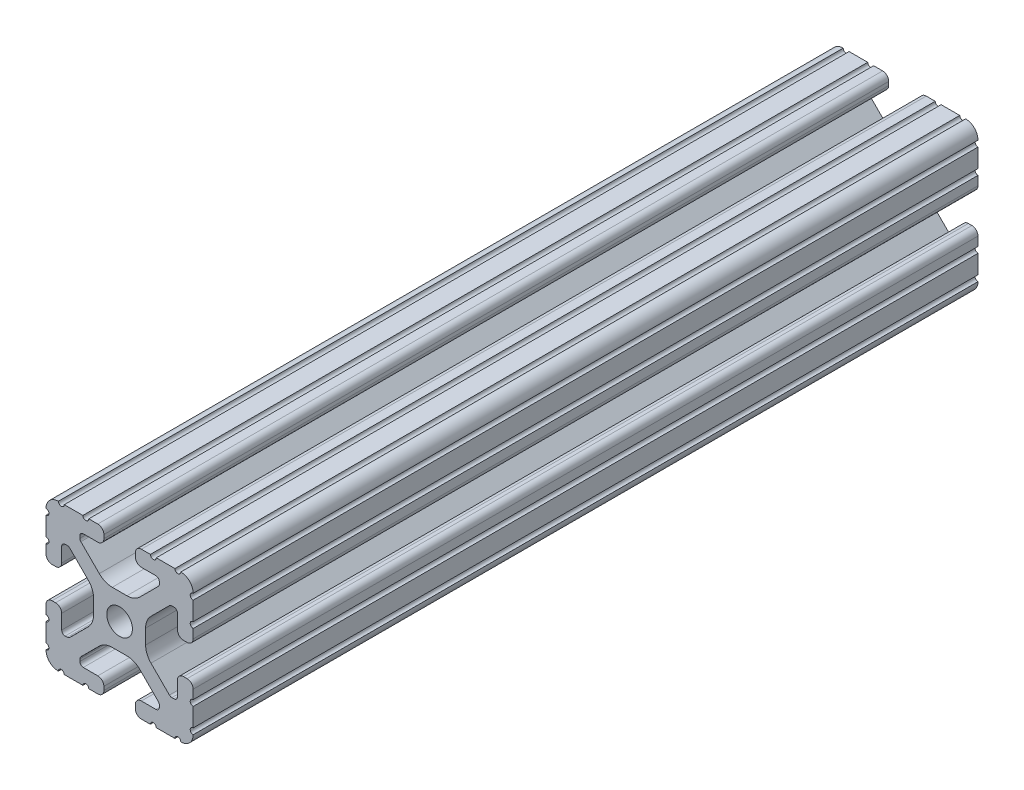
SolidWorks part; units mm, degrees
material "6105-T5 Aluminum"
ref_plane "Front Plane" through (0, 0, 0) normal (0, 0, 1) x (1, 0, 0)
ref_plane "Top Plane" through (0, 0, 0) normal (0, 1, 0) x (1, 0, 0)
ref_plane "Right Plane" through (0, 0, 0) normal (1, 0, 0) x (0, 0, -1)
sketch "Sketch1" plane through (0, 0, 0) normal (0, 0, 1) x (1, 0, 0)
  line L0 (-14.097, 10.287) -> (-13.5289, 10.287)
  line L1 (-12.9003, 10.0266) -> (-8.1292, 5.2555)
  line L2 (-6.738, 1.8969) -> (-6.738, -1.8969)
  line L3 (-8.1292, -5.2555) -> (-12.9003, -10.0266)
  line L4 (-13.5289, -10.287) -> (-14.097, -10.287)
  line L5 (-14.986, -9.398) -> (-14.986, -5.6388)
  line L6 (-16.5608, -4.064) -> (-17.4752, -4.064)
  line L7 (-19.05, -5.6388) -> (-19.05, -7.9756)
  line L8 (-19.05, -9.4996) -> (-19.05, -14.3256)
  line L9 (-19.05, -15.8496) -> (-19.05, -15.875)
  line L10 (-15.875, -19.05) -> (-15.8496, -19.05)
  line L11 (-14.3256, -19.05) -> (-9.4996, -19.05)
  line L12 (-7.9756, -19.05) -> (-5.6388, -19.05)
  line L13 (-4.064, -17.4752) -> (-4.064, -16.5608)
  line L14 (-5.6388, -14.986) -> (-9.398, -14.986)
  line L15 (-10.287, -14.097) -> (-10.287, -13.5289)
  line L16 (-10.0266, -12.9003) -> (-5.2555, -8.1292)
  line L17 (-1.8969, -6.738) -> (1.8969, -6.738)
  line L18 (5.2555, -8.1292) -> (10.0266, -12.9003)
  line L19 (10.287, -13.5289) -> (10.287, -14.097)
  line L20 (9.398, -14.986) -> (5.6388, -14.986)
  line L21 (4.064, -16.5608) -> (4.064, -17.4752)
  line L22 (5.6388, -19.05) -> (7.9756, -19.05)
  line L23 (9.4996, -19.05) -> (14.3256, -19.05)
  line L24 (15.8496, -19.05) -> (15.875, -19.05)
  line L25 (19.05, -15.875) -> (19.05, -15.8496)
  line L26 (19.05, -14.3256) -> (19.05, -9.4996)
  line L27 (19.05, -7.9756) -> (19.05, -5.6388)
  line L28 (17.4752, -4.064) -> (16.5608, -4.064)
  line L29 (14.986, -5.6388) -> (14.986, -9.398)
  line L30 (14.097, -10.287) -> (13.5289, -10.287)
  line L31 (12.9003, -10.0266) -> (8.1292, -5.2555)
  line L32 (6.738, -1.8969) -> (6.738, 1.8969)
  line L33 (8.1292, 5.2555) -> (12.9003, 10.0266)
  line L34 (13.5289, 10.287) -> (14.097, 10.287)
  line L35 (14.986, 9.398) -> (14.986, 5.6388)
  line L36 (16.5608, 4.064) -> (17.4752, 4.064)
  line L37 (19.05, 5.6388) -> (19.05, 7.9756)
  line L38 (19.05, 9.4996) -> (19.05, 14.3256)
  line L39 (19.05, 15.8496) -> (19.05, 15.875)
  line L40 (15.875, 19.05) -> (15.8496, 19.05)
  line L41 (14.3256, 19.05) -> (9.4996, 19.05)
  line L42 (7.9756, 19.05) -> (5.6388, 19.05)
  line L43 (4.064, 17.4752) -> (4.064, 16.5608)
  line L44 (5.6388, 14.986) -> (9.398, 14.986)
  line L45 (10.287, 14.097) -> (10.287, 13.5289)
  line L46 (10.0266, 12.9003) -> (5.2555, 8.1292)
  line L47 (1.8969, 6.738) -> (-1.8969, 6.738)
  line L48 (-5.2555, 8.1292) -> (-10.0266, 12.9003)
  line L49 (-10.287, 13.5289) -> (-10.287, 14.097)
  line L50 (-9.398, 14.986) -> (-5.6388, 14.986)
  line L51 (-4.064, 16.5608) -> (-4.064, 17.4752)
  line L52 (-5.6388, 19.05) -> (-7.9756, 19.05)
  line L53 (-9.4996, 19.05) -> (-14.3256, 19.05)
  line L54 (-15.8496, 19.05) -> (-15.875, 19.05)
  line L55 (-19.05, 15.875) -> (-19.05, 15.8496)
  line L56 (-19.05, 14.3256) -> (-19.05, 9.4996)
  line L57 (-19.05, 7.9756) -> (-19.05, 5.6388)
  line L58 (-17.4752, 4.064) -> (-16.5608, 4.064)
  line L59 (-14.986, 5.6388) -> (-14.986, 9.398)
  circle A0 centre (0, 0) radius 3.3274
  arc A1 (-14.097, 10.287) -> (-14.986, 9.398) centre (-14.097, 9.398) ccw
  arc A2 (-12.9003, 10.0266) -> (-13.5289, 10.287) centre (-13.5289, 9.398) ccw
  arc A3 (-6.738, 1.8969) -> (-8.1292, 5.2555) centre (-11.4878, 1.8969) ccw
  arc A4 (-8.1292, -5.2555) -> (-6.738, -1.8969) centre (-11.4878, -1.8969) ccw
  arc A5 (-13.5289, -10.287) -> (-12.9003, -10.0266) centre (-13.5289, -9.398) ccw
  arc A6 (-14.986, -9.398) -> (-14.097, -10.287) centre (-14.097, -9.398) ccw
  arc A7 (-14.986, -5.6388) -> (-16.5608, -4.064) centre (-16.5608, -5.6388) ccw
  arc A8 (-17.4752, -4.064) -> (-19.05, -5.6388) centre (-17.4752, -5.6388) ccw
  arc A9 (-19.05, -9.4996) -> (-19.05, -7.9756) centre (-19.05, -8.7376) ccw
  arc A10 (-19.05, -15.8496) -> (-19.05, -14.3256) centre (-19.05, -15.0876) ccw
  arc A11 (-19.05, -15.875) -> (-15.875, -19.05) centre (-15.875, -15.875) ccw
  arc A12 (-14.3256, -19.05) -> (-15.8496, -19.05) centre (-15.0876, -19.05) ccw
  arc A13 (-7.9756, -19.05) -> (-9.4996, -19.05) centre (-8.7376, -19.05) ccw
  arc A14 (-5.6388, -19.05) -> (-4.064, -17.4752) centre (-5.6388, -17.4752) ccw
  arc A15 (-4.064, -16.5608) -> (-5.6388, -14.986) centre (-5.6388, -16.5608) ccw
  arc A16 (-10.287, -14.097) -> (-9.398, -14.986) centre (-9.398, -14.097) ccw
  arc A17 (-10.0266, -12.9003) -> (-10.287, -13.5289) centre (-9.398, -13.5289) ccw
  arc A18 (-1.8969, -6.738) -> (-5.2555, -8.1292) centre (-1.8969, -11.4878) ccw
  arc A19 (5.2555, -8.1292) -> (1.8969, -6.738) centre (1.8969, -11.4878) ccw
  arc A20 (10.287, -13.5289) -> (10.0266, -12.9003) centre (9.398, -13.5289) ccw
  arc A21 (9.398, -14.986) -> (10.287, -14.097) centre (9.398, -14.097) ccw
  arc A22 (5.6388, -14.986) -> (4.064, -16.5608) centre (5.6388, -16.5608) ccw
  arc A23 (4.064, -17.4752) -> (5.6388, -19.05) centre (5.6388, -17.4752) ccw
  arc A24 (9.4996, -19.05) -> (7.9756, -19.05) centre (8.7376, -19.05) ccw
  arc A25 (15.8496, -19.05) -> (14.3256, -19.05) centre (15.0876, -19.05) ccw
  arc A26 (15.875, -19.05) -> (19.05, -15.875) centre (15.875, -15.875) ccw
  arc A27 (19.05, -14.3256) -> (19.05, -15.8496) centre (19.05, -15.0876) ccw
  arc A28 (19.05, -7.9756) -> (19.05, -9.4996) centre (19.05, -8.7376) ccw
  arc A29 (19.05, -5.6388) -> (17.4752, -4.064) centre (17.4752, -5.6388) ccw
  arc A30 (16.5608, -4.064) -> (14.986, -5.6388) centre (16.5608, -5.6388) ccw
  arc A31 (14.097, -10.287) -> (14.986, -9.398) centre (14.097, -9.398) ccw
  arc A32 (12.9003, -10.0266) -> (13.5289, -10.287) centre (13.5289, -9.398) ccw
  arc A33 (6.738, -1.8969) -> (8.1292, -5.2555) centre (11.4878, -1.8969) ccw
  arc A34 (8.1292, 5.2555) -> (6.738, 1.8969) centre (11.4878, 1.8969) ccw
  arc A35 (13.5289, 10.287) -> (12.9003, 10.0266) centre (13.5289, 9.398) ccw
  arc A36 (14.986, 9.398) -> (14.097, 10.287) centre (14.097, 9.398) ccw
  arc A37 (14.986, 5.6388) -> (16.5608, 4.064) centre (16.5608, 5.6388) ccw
  arc A38 (17.4752, 4.064) -> (19.05, 5.6388) centre (17.4752, 5.6388) ccw
  arc A39 (19.05, 9.4996) -> (19.05, 7.9756) centre (19.05, 8.7376) ccw
  arc A40 (19.05, 15.8496) -> (19.05, 14.3256) centre (19.05, 15.0876) ccw
  arc A41 (19.05, 15.875) -> (15.875, 19.05) centre (15.875, 15.875) ccw
  arc A42 (14.3256, 19.05) -> (15.8496, 19.05) centre (15.0876, 19.05) ccw
  arc A43 (7.9756, 19.05) -> (9.4996, 19.05) centre (8.7376, 19.05) ccw
  arc A44 (5.6388, 19.05) -> (4.064, 17.4752) centre (5.6388, 17.4752) ccw
  arc A45 (4.064, 16.5608) -> (5.6388, 14.986) centre (5.6388, 16.5608) ccw
  arc A46 (10.287, 14.097) -> (9.398, 14.986) centre (9.398, 14.097) ccw
  arc A47 (10.0266, 12.9003) -> (10.287, 13.5289) centre (9.398, 13.5289) ccw
  arc A48 (1.8969, 6.738) -> (5.2555, 8.1292) centre (1.8969, 11.4878) ccw
  arc A49 (-5.2555, 8.1292) -> (-1.8969, 6.738) centre (-1.8969, 11.4878) ccw
  arc A50 (-10.287, 13.5289) -> (-10.0266, 12.9003) centre (-9.398, 13.5289) ccw
  arc A51 (-9.398, 14.986) -> (-10.287, 14.097) centre (-9.398, 14.097) ccw
  arc A52 (-5.6388, 14.986) -> (-4.064, 16.5608) centre (-5.6388, 16.5608) ccw
  arc A53 (-4.064, 17.4752) -> (-5.6388, 19.05) centre (-5.6388, 17.4752) ccw
  arc A54 (-9.4996, 19.05) -> (-7.9756, 19.05) centre (-8.7376, 19.05) ccw
  arc A55 (-15.8496, 19.05) -> (-14.3256, 19.05) centre (-15.0876, 19.05) ccw
  arc A56 (-15.875, 19.05) -> (-19.05, 15.875) centre (-15.875, 15.875) ccw
  arc A57 (-19.05, 14.3256) -> (-19.05, 15.8496) centre (-19.05, 15.0876) ccw
  arc A58 (-19.05, 7.9756) -> (-19.05, 9.4996) centre (-19.05, 8.7376) ccw
  arc A59 (-19.05, 5.6388) -> (-17.4752, 4.064) centre (-17.4752, 5.6388) ccw
  arc A60 (-16.5608, 4.064) -> (-14.986, 5.6388) centre (-16.5608, 5.6388) ccw
extrude "Boss-Extrude1" add sketch "Sketch1" along normal blind 203.2
